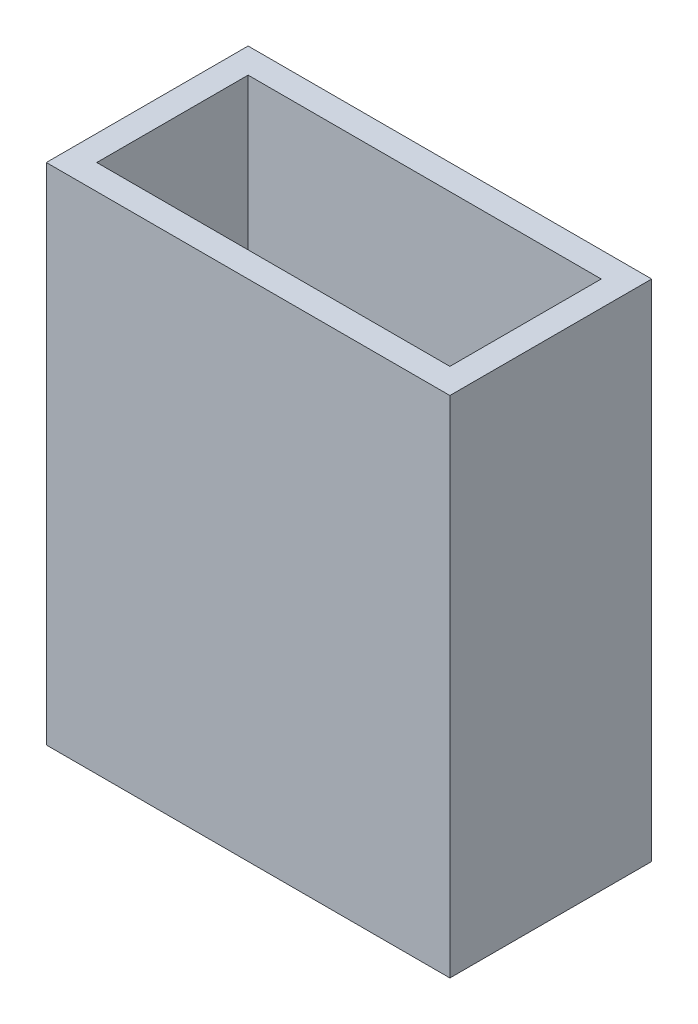
SolidWorks part; units mm, degrees
material "1060 Alloy"
ref_plane "Front Plane" through (0, 0, 0) normal (0, 0, 1) x (1, 0, 0)
ref_plane "Top Plane" through (0, 0, 0) normal (0, 1, 0) x (1, 0, 0)
ref_plane "Right Plane" through (0, 0, 0) normal (1, 0, 0) x (0, 0, -1)
sketch "Sketch1" plane through (0, 0, 0) normal (0, 1, 0) x (1, 0, 0)
  line L1 (-25.4, -12.7) -> (25.4, -12.7)
  line L2 (-25.4, -12.7) -> (-25.4, 12.7)
  line L3 (-25.4, 12.7) -> (25.4, 12.7)
  line L4 (25.4, -12.7) -> (25.4, 12.7)
  line L5 (-25.4, -12.7) -> (25.4, 12.7) construction
  line L6 (-25.4, 12.7) -> (25.4, -12.7) construction
  point P0 (0, 0)
  dimension "D1" = 50.8
  dimension "D2" = 25.4
extrude "Extrude-Thin1" add sketch "Sketch1" along normal blind 63.5 thin thin type one direction reverse wall 3.175
